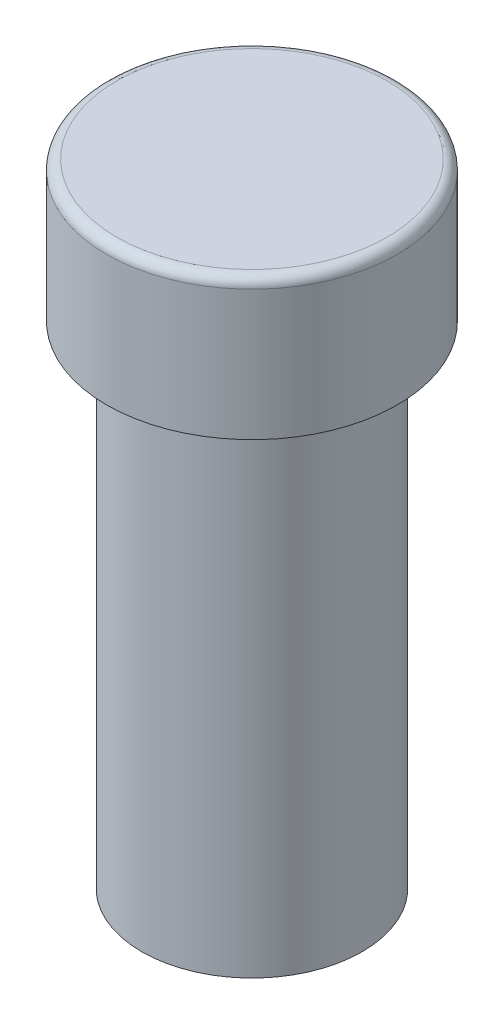
SolidWorks part; units mm, degrees
ref_plane "前视基准面" through (0, 0, 0) normal (0, 0, 1) x (1, 0, 0)
ref_plane "上视基准面" through (0, 0, 0) normal (0, 1, 0) x (1, 0, 0)
ref_plane "右视基准面" through (0, 0, 0) normal (1, 0, 0) x (0, 0, -1)
sketch "草图2" plane through (0, 0, 0) normal (0, 1, 0) x (1, 0, 0)
  circle A0 centre (0, 0) radius 14.5
  dimension "D1" = 29
extrude "凸台-拉伸1" add sketch "草图2" along normal blind 14
sketch "草图3" plane through (0, 0, 0) normal (0, -1, 0) x (1, 0, 0)
  circle A0 centre (0, 0) radius 11
  dimension "D1" = 22
extrude "凸台-拉伸2" add sketch "草图3" along normal offset from surface (49 mm away) 63 up to face at (0, 14, 14.5)
fillet "圆角1" radius 1 1 edges at (0, 14, 14.5)
